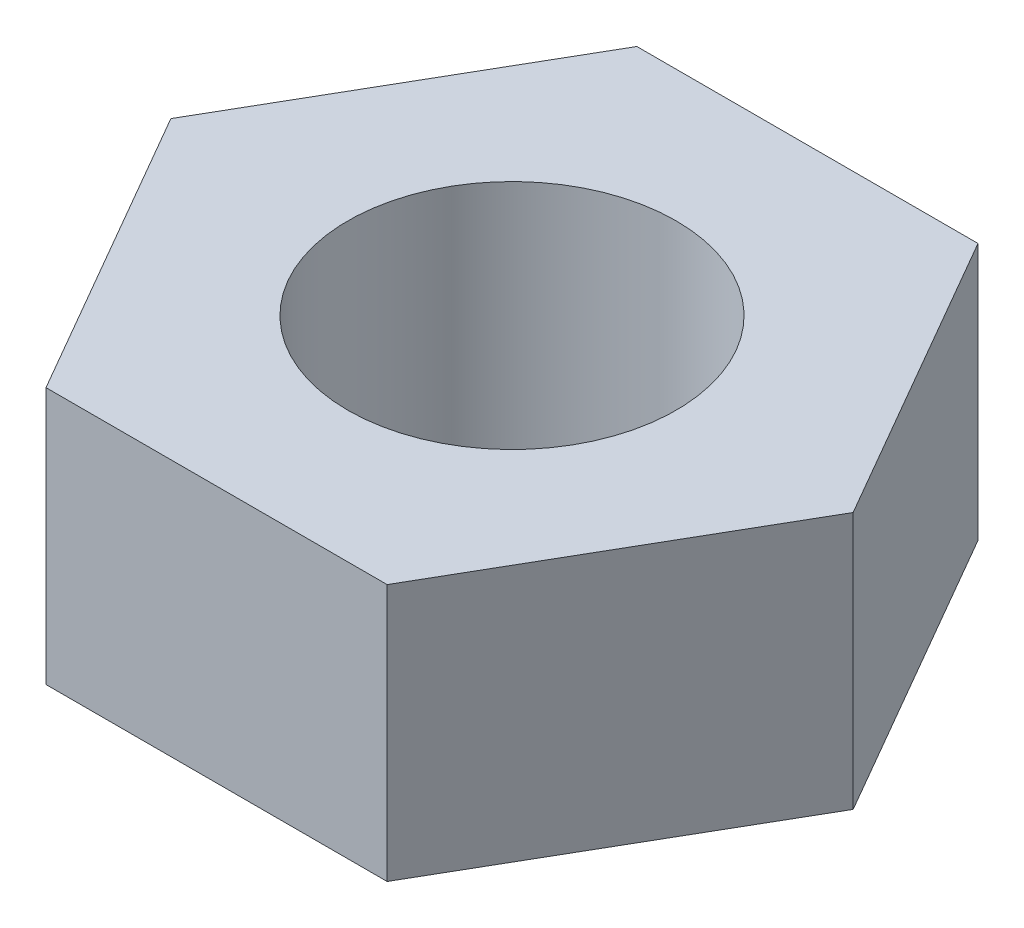
SolidWorks part; units mm, degrees
ref_plane "Спереди" through (0, 0, 0) normal (0, 0, 1) x (1, 0, 0)
ref_plane "Сверху" through (0, 0, 0) normal (0, 1, 0) x (1, 0, 0)
ref_plane "Справа" through (0, 0, 0) normal (1, 0, 0) x (0, 0, -1)
sketch "Sketch1" plane through (0, 0, 0) normal (0, 1, 0) x (1, 0, 0)
  line L1 (1.5588, -2.7) -> (3.1177, 0)
  line L2 (3.1177, 0) -> (1.5588, 2.7)
  line L3 (1.5588, 2.7) -> (-1.5588, 2.7)
  line L4 (-1.5588, 2.7) -> (-3.1177, 0)
  line L5 (-3.1177, 0) -> (-1.5588, -2.7)
  line L6 (-1.5588, -2.7) -> (1.5588, -2.7)
  circle A0 centre (0, 0) radius 2.7 construction
  circle A1 centre (0, 0) radius 1.5
  dimension "D1" = 3
  dimension "D2" = 5.4
extrude "Boss-Extrude1" add sketch "Sketch1" along normal blind 2.35
